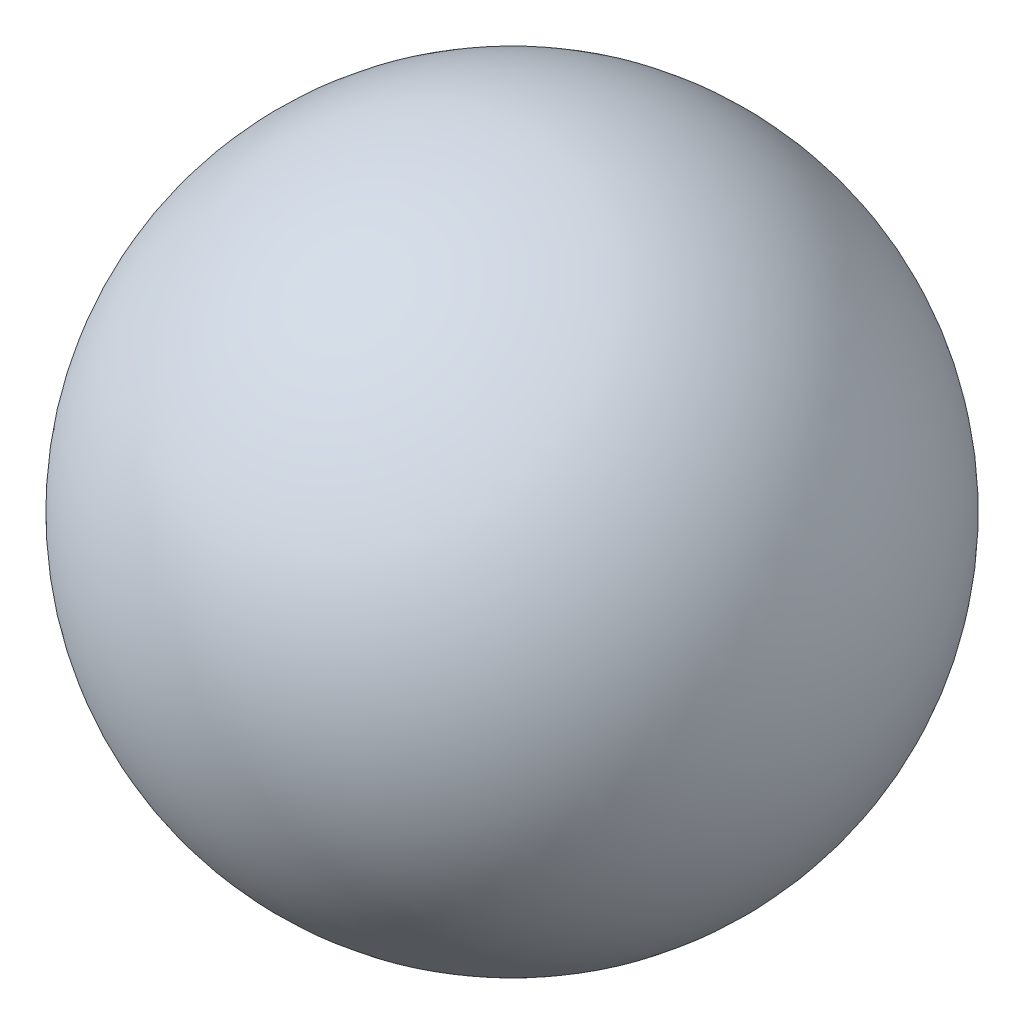
SolidWorks part; units mm, degrees
material "1.4511 (X3CrNb17)"
ref_plane "前视基准面" through (0, 0, 0) normal (0, 0, 1) x (1, 0, 0)
ref_plane "上视基准面" through (0, 0, 0) normal (0, 1, 0) x (1, 0, 0)
ref_plane "右视基准面" through (0, 0, 0) normal (1, 0, 0) x (0, 0, -1)
sketch "草图1" plane through (0, 0, 0) normal (0, 0, 1) x (1, 0, 0)
  line L0 (0, 0.625) -> (0, -0.625)
  arc A0 (0, -0.625) -> (0, 0.625) centre (0, 0) ccw
  dimension "D1" = 1.25
revolve "旋转1" add sketch "草图1" angle 360 about L0
